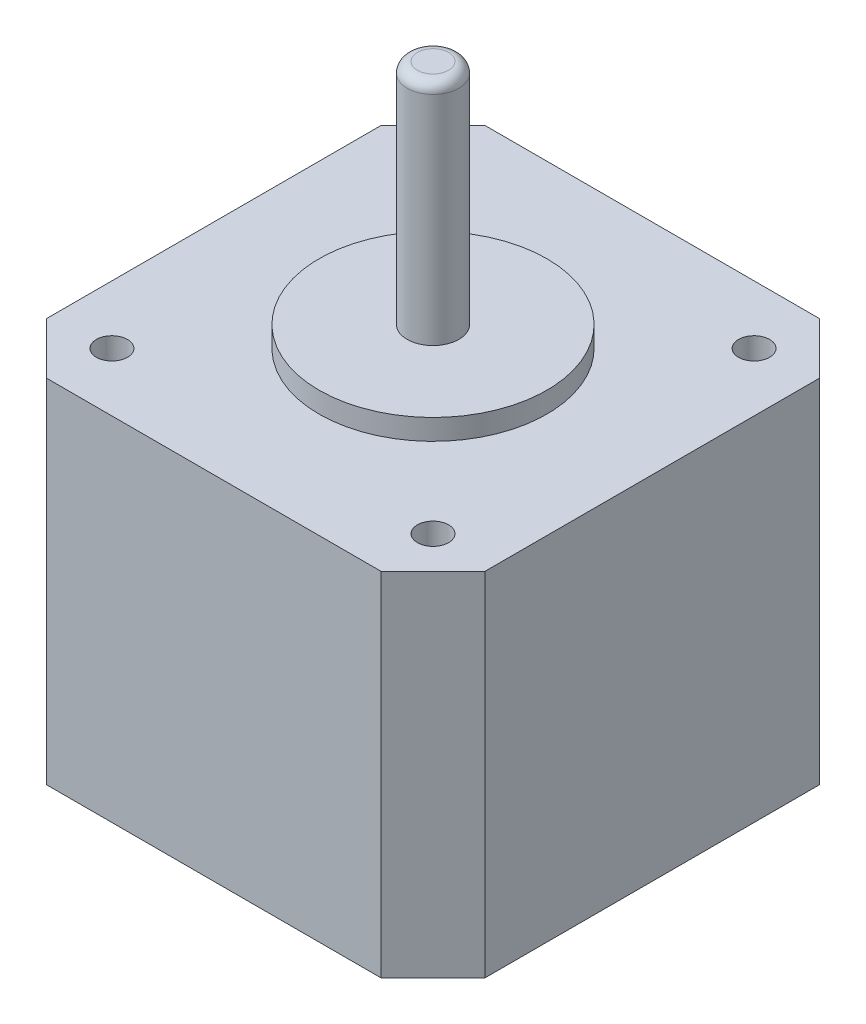
SolidWorks part; units mm, degrees
ref_plane "Front" through (0, 0, 0) normal (0, 0, 1) x (1, 0, 0)
ref_plane "Top" through (0, 0, 0) normal (0, 1, 0) x (1, 0, 0)
ref_plane "Right" through (0, 0, 0) normal (1, 0, 0) x (0, 0, -1)
sketch "Sketch1" plane through (0, 0, 0) normal (0, 1, 0) x (1, 0, 0)
  line L1 (-21.15, -21.15) -> (21.15, -21.15)
  line L2 (-21.15, -21.15) -> (-21.15, 21.15)
  line L3 (-21.15, 21.15) -> (21.15, 21.15)
  line L4 (21.15, -21.15) -> (21.15, 21.15)
  line L5 (-21.15, -21.15) -> (21.15, 21.15) construction
  line L6 (-21.15, 21.15) -> (21.15, -21.15) construction
  point P0 (0, 0)
  dimension "D1" = 42.3
extrude "Boss-Extrude1" add sketch "Sketch1" along normal blind 34
sketch "Sketch2" plane through (0, 34, 0) normal (0, 1, 0) x (1, 0, 0)
  circle A0 centre (0, 0) radius 2.5
  dimension "D1" = 5
extrude "Boss-Extrude2" add sketch "Sketch2" along normal blind 24
sketch "Sketch3" plane through (0, 34, 0) normal (0, 1, 0) x (1, 0, 0)
  circle A0 centre (0, 0) radius 11
  dimension "D1" = 22
extrude "Boss-Extrude3" add sketch "Sketch3" along normal blind 2
sketch "Sketch4" plane through (0, 34, 0) normal (0, 1, 0) x (1, 0, 0)
  line L0 (-15.5, 15.5) -> (15.5, 15.5) construction
  line L1 (15.5, 15.5) -> (15.5, -15.5) construction
  line L2 (0, 21.15) -> (0, 15.5) construction
  line L3 (21.15, 21.15) -> (-21.15, 21.15) construction
  line L4 (15.5, 0) -> (21.15, 0) construction
  line L5 (21.15, -21.15) -> (21.15, 21.15) construction
  circle A0 centre (-15.5, 15.5) radius 1.5
  circle A1 centre (15.5, 15.5) radius 1.5
  circle A2 centre (15.5, -15.5) radius 1.5
  circle A3 centre (-15.5, -15.5) radius 1.5
  point P16 (0, 0)
  dimension "D1" = 3
  dimension "D2" = 31
  dimension "D3" = 31
extrude "Cut-Extrude1" cut sketch "Sketch4" against normal blind 4.5
chamfer "Chamfer1" distance 5 angle 45 4 edges at (21.15, 17, -21.15) (-21.15, 17, -21.15) (-21.15, 17, 21.15) (21.15, 17, 21.15)
fillet "Fillet1" radius 1 1 edges at (0, 58, 2.5)
